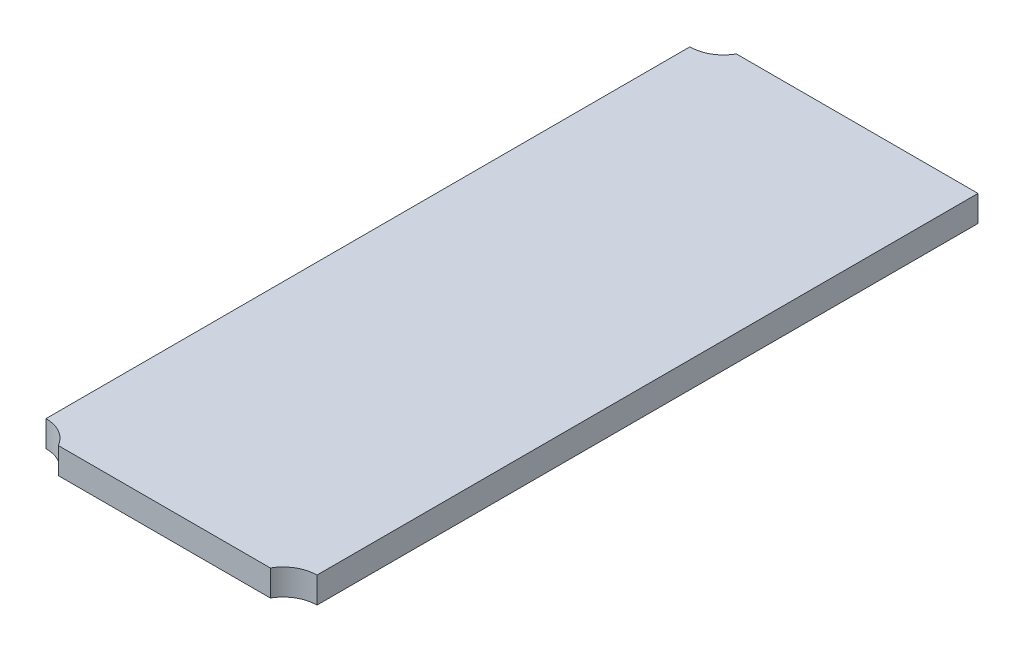
SolidWorks part; units mm, degrees
ref_plane "前视基准面" through (0, 0, 0) normal (0, 0, 1) x (1, 0, 0)
ref_plane "上视基准面" through (0, 0, 0) normal (0, 1, 0) x (1, 0, 0)
ref_plane "右视基准面" through (0, 0, 0) normal (1, 0, 0) x (0, 0, -1)
other "Configuration Table"
sketch "草图1" plane through (0, 0, 0) normal (0, 1, 0) x (1, 0, 0)
  line L0 (16, 103) -> (16, 0) construction
  line L1 (0, 0) -> (32, 0)
  line L2 (0, 0) -> (0, 103)
  line L3 (0, 103) -> (32, 103)
  line L4 (32, 0) -> (32, 103)
  line L5 (3, 3) -> (29, 3) construction
  line L6 (3, 3) -> (3, 71.27) construction
  line L7 (29, 3) -> (29, 100.07) construction
  circle A0 centre (3, 3) radius 1.6
  circle A1 centre (29, 3) radius 1.6
  circle A2 centre (3, 71.27) radius 1.6
  circle A3 centre (29, 100.07) radius 1.6
  dimension "D5" = 3.2
  dimension "D6" = 3.2
  dimension "D7" = 68.27
  dimension "D9" = 3.2
  dimension "D1" = 32
  dimension "D2" = 103
  dimension "D3" = 26
  dimension "D4" = 3
  dimension "D8" = 97.07
extrude "凸台-拉伸1" add sketch "草图1" along normal blind 2.5
sketch "草图2" plane through (0, 2.5, 0) normal (0, 1, 0) x (1, 0, 0)
  line L0 (3, 68.02) -> (3, 6.25)
  line L1 (5.8289, 4.6) -> (26.1711, 4.6)
  line L2 (29, 6.25) -> (29, 69.67)
  line L3 (29, 69.67) -> (5.8289, 69.67)
  line L19 (0, 103) -> (0, 0)
  line L20 (0, 0) -> (32, 0)
  line L21 (32, 0) -> (32, 103)
  line L22 (32, 103) -> (0, 103)
  line L23 (0, 103) -> (0, 0)
  line L24 (0, 0) -> (32, 0)
  line L25 (32, 0) -> (32, 103)
  line L26 (32, 103) -> (0, 103)
  arc A4 (5.8289, 4.6) -> (3, 6.25) centre (3, 3) ccw
  arc A5 (29, 6.25) -> (26.1711, 4.6) centre (29, 3) ccw
  arc A6 (3, 68.02) -> (5.8289, 69.67) centre (3, 71.27) ccw
  dimension "D1" = 3.25
  dimension "D4" = 3.25
  dimension "D5" = 3.25
  dimension "D2" = 4.6
  dimension "D6" = 63.42
  dimension "D3" = 0
extrude "切除-拉伸1" cut sketch "草图2" against normal through all
sketch "草图3" plane through (0, 2.5, 0) normal (0, 1, 0) x (1, 0, 0)
  line L0 (3, 37.135) -> (29, 37.135) construction
  line L1 (3, 68.02) -> (3, 6.25) construction
  line L4 (29, 6.25) -> (29, 69.67) construction
  text T0 "为所有人\r\n" font "华光标题黑_CNKI" height 3.5
  point P3 (0, 0)
  point P6 (0, 0)
